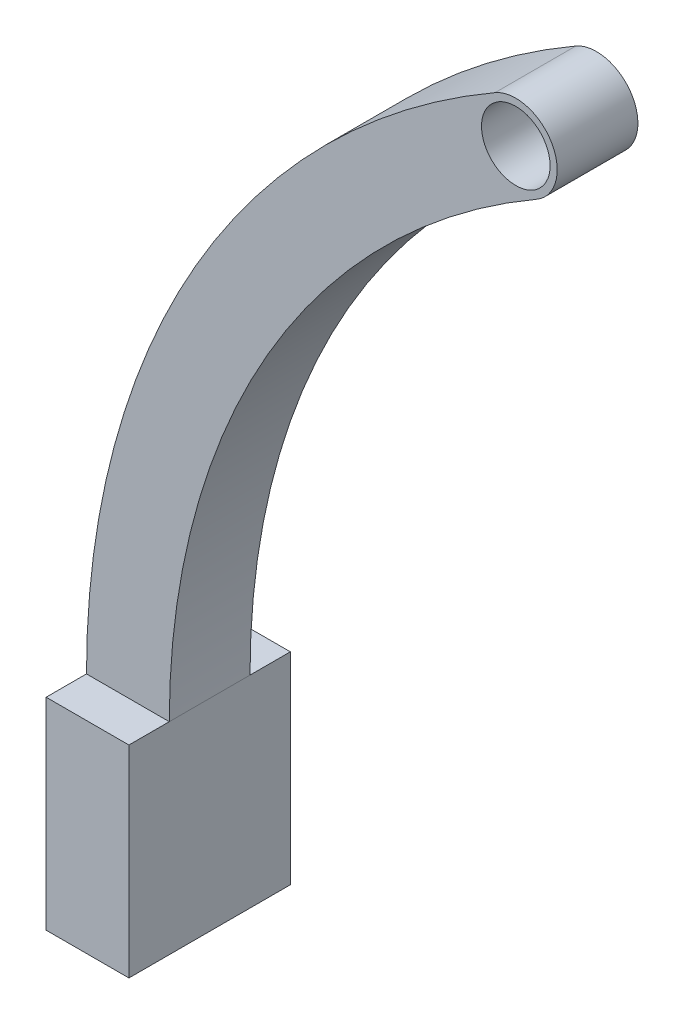
SolidWorks part; units mm, degrees
ref_plane "前视基准面" through (0, 0, 0) normal (0, 0, 1) x (1, 0, 0)
ref_plane "上视基准面" through (0, 0, 0) normal (0, 1, 0) x (1, 0, 0)
ref_plane "右视基准面" through (0, 0, 0) normal (1, 0, 0) x (0, 0, -1)
sketch "草图1" plane through (0, 0, 0) normal (0, 0, 1) x (1, 0, 0)
  line L0 (-477.4765, 0) -> (471.1662, 0) construction
  line L1 (0, -420.9044) -> (0, 480.7233) construction
  line L2 (0, 0) -> (-181.9861, 315.2092) construction
  line L3 (-181.9861, 315.2092) -> (-202.5, 350.7403) construction
  line L4 (-363.9723, 0) -> (-405, 0)
  line L5 (-405, 0) -> (-405.9185, -3.2631)
  arc A0 (-181.9861, 315.2092) -> (-363.9723, 0) centre (0, 0) ccw construction
  arc A1 (-181.9861, 315.2092) -> (-363.9723, 0) centre (0, 0) ccw
  arc A2 (-202.5, 350.7403) -> (-405, 0) centre (0, 0) ccw
  arc A3 (-181.9861, 315.2092) -> (-202.5, 350.7403) centre (-192.2431, 332.9748) ccw
  circle A4 centre (-192.2431, 332.9748) radius 17
  dimension "D1" = 34
  dimension "D3" = 810
  dimension "D2" = 30
extrude "凸台-拉伸1" add sketch "草图1" along normal blind 40 contours A1 A3 A2 L4 A4
sketch "草图2" plane through (0, 0, 0) normal (0, 0, 1) x (1, 0, 0)
  line L0 (-405, 0) -> (-405, -100)
  line L1 (-405, -100) -> (-363.9723, -100)
  line L2 (-363.9723, -100) -> (-363.9723, 0)
  line L3 (-363.9723, 0) -> (-405, 0)
  dimension "D1" = 100
extrude "凸台-拉伸2" add sketch "草图2" along normal blind 60 and the other way blind 20
